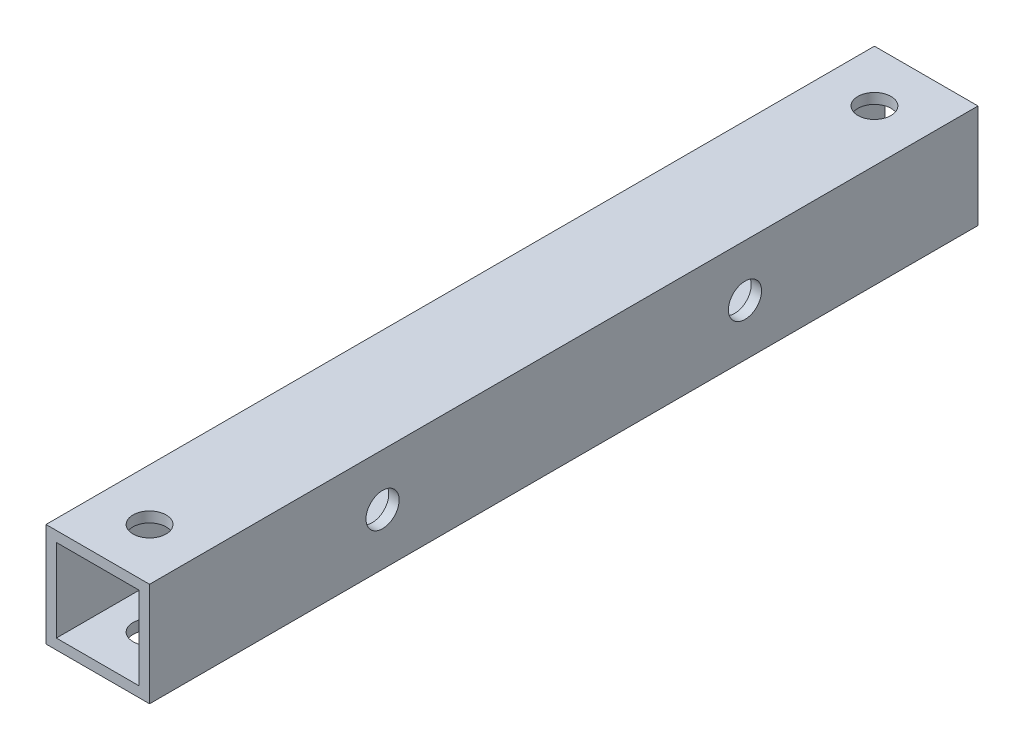
SolidWorks part; units mm, degrees
material "6061 合金"
ref_plane "正面" through (0, 0, 0) normal (0, 0, 1) x (1, 0, 0)
ref_plane "平面" through (0, 0, 0) normal (0, 1, 0) x (1, 0, 0)
ref_plane "右側面" through (0, 0, 0) normal (1, 0, 0) x (0, 0, -1)
sketch "断面 スケッチ" plane through (0, 0, 0) normal (0, 0, 1) x (1, 0, 0)
  line L1 (-5, -5) -> (5, -5)
  line L2 (-5, -5) -> (-5, 5)
  line L3 (-5, 5) -> (5, 5)
  line L4 (5, -5) -> (5, 5)
  line L5 (-5, -5) -> (5, 5) construction
  line L6 (-5, 5) -> (5, -5) construction
  point P0 (0, 0)
  dimension "D1" = 10
extrude "フレーム全長" add sketch "断面 スケッチ" along normal blind 80 thin thin type one direction reverse wall 1
sketch "上面穴 スケッチ" plane through (0, 5, 0) normal (0, 1, 0) x (1, 0, 0)
  line L0 (0, 0) -> (0, -80) construction
  line L1 (5, 0) -> (-5, 0) construction
  line L2 (5, -80) -> (-5, -80) construction
  line L3 (-5, -40) -> (5, -40) construction
  line L4 (-5, -80) -> (-5, 0) construction
  line L5 (5, -80) -> (5, 0) construction
  circle A0 centre (0, -5) radius 1.6
  circle A1 centre (0, -75) radius 1.6
  dimension "D1" = 5
  dimension "D2" = 3.2
sketch "側面穴 スケッチ" plane through (5, 0, 0) normal (1, 0, 0) x (0, 0, -1)
  line L0 (0, 0) -> (-80, 0) construction
  line L1 (0, -5) -> (0, 5) construction
  line L2 (-80, -5) -> (-80, 5) construction
  line L3 (-40, 5) -> (-40, -5) construction
  line L4 (-80, 5) -> (0, 5) construction
  line L5 (-80, -5) -> (0, -5) construction
  circle A0 centre (-22.5, 0) radius 1.6
  circle A1 centre (-57.5, 0) radius 1.6
  dimension "D1" = 22.5
  dimension "D2" = 3.2
extrude "上面穴貫通" cut sketch "上面穴 スケッチ" against normal through all
extrude "側面穴貫通" cut sketch "側面穴 スケッチ" against normal through all
fillet "フィレット" [suppressed] radius 5
